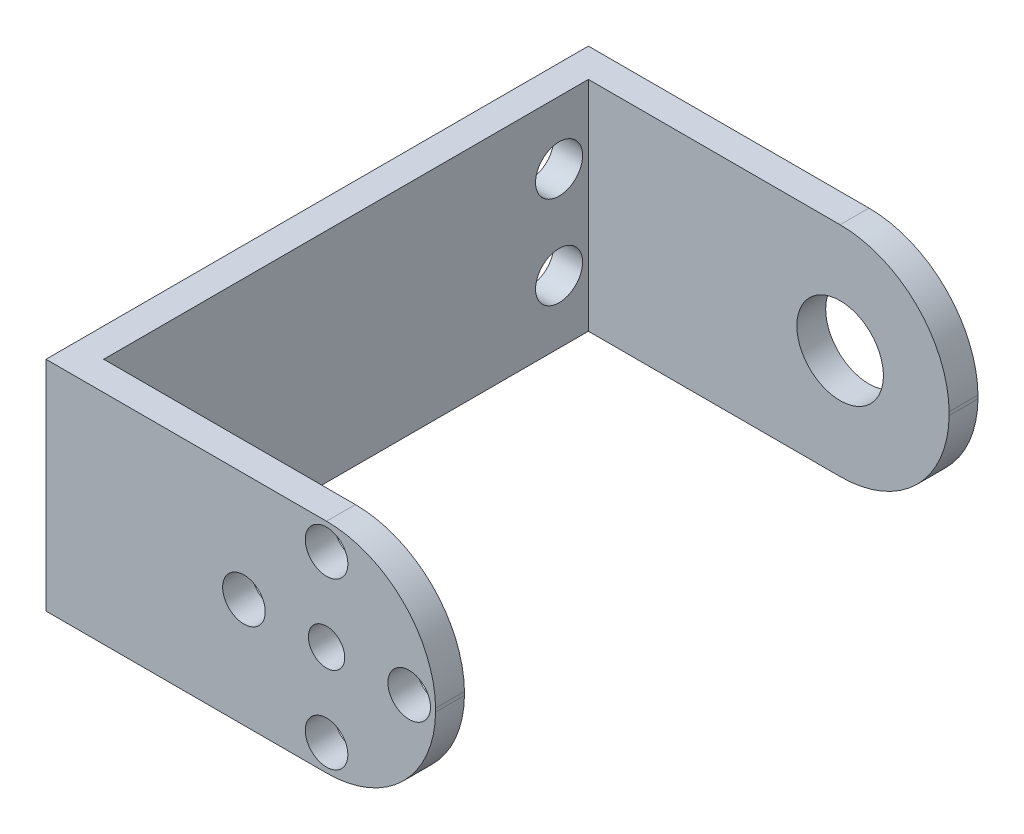
SolidWorks part; units mm, degrees
ref_plane "Front Plane" through (0, 0, 0) normal (0, 0, 1) x (1, 0, 0)
ref_plane "Top Plane" through (0, 0, 0) normal (0, 1, 0) x (1, 0, 0)
ref_plane "Right Plane" through (0, 0, 0) normal (1, 0, 0) x (0, 0, -1)
sketch "Sketch1" plane through (0, 0, 0) normal (0, 1, 0) x (1, 0, 0)
  line L0 (-21.4375, 0) -> (21.4375, 0) construction
  line L1 (21.4375, -29.845) -> (-21.4375, -29.845)
  line L2 (21.4375, -29.845) -> (21.4375, 29.845)
  line L3 (21.4375, 29.845) -> (-21.4375, 29.845)
  line L4 (-21.4375, -29.845) -> (-21.4375, 29.845)
  line L5 (21.4375, -29.845) -> (-21.4375, 29.845) construction
  line L6 (21.4375, 29.845) -> (-21.4375, -29.845) construction
  line L8 (21.4375, -26.67) -> (-18.2625, -26.67)
  line L10 (21.4375, 26.67) -> (-18.2625, 26.67)
  line L11 (-18.2625, -26.67) -> (-18.2625, 26.67)
  line L12 (19.9408, -16.2583) -> (-18.2625, 26.67) construction
  line L13 (13.9323, 9.5067) -> (-18.2625, -26.67) construction
  point P0 (0, 0)
  point P8 (5.472, 0)
  point P15 (-18.2625, 0)
  dimension "D1" = 59.69
  dimension "D2" = 42.875
  dimension "D3" = 53.34
  dimension "D4" = 39.7
extrude "Boss-Extrude1" add sketch "Sketch1" along normal blind 24.003 contours L8 L11 L10 L2 L3 L4 L1
sketch "Sketch2" plane through (0, 0, 29.845) normal (0, 0, 1) x (1, 0, 0)
  line L0 (-21.4375, 12.0015) -> (21.4375, 12.0015) construction
  line L1 (-21.4375, 24.003) -> (-21.4375, 0) construction
  line L2 (21.4375, 24.003) -> (21.4375, 0) construction
  line L3 (21.4375, 0) -> (-21.4375, 0) construction
  line L4 (21.4375, 24.003) -> (-21.4375, 24.003) construction
  line L5 (9.4375, 0) -> (15.0875, 0)
  line L7 (15.0875, 24.003) -> (9.4375, 24.003)
  arc A0 (9.4375, 0) -> (9.4375, 24.003) centre (9.4375, 12.0015) ccw
  point P6 (9.4375, 12.0015)
  dimension "D1" = 12
extrude "Cut-Extrude1" cut sketch "Sketch2" against normal through all
sketch "Sketch3" plane through (0, 0, 29.845) normal (0, 0, 1) x (1, 0, 0)
  line L0 (9.4375, 0) -> (9.4375, 24.003) construction
  circle A0 centre (9.4375, 12.0015) radius 2
  circle A1 centre (9.4375, 21.0947) radius 2.3432
  circle A2 centre (18.5307, 12.0015) radius 2.3432
  circle A3 centre (9.4375, 2.9083) radius 2.3432
  circle A4 centre (0.3443, 12.0015) radius 2.3432
  point P17 (3.0868, 12.0007)
  point P18 (9.4375, 12.0015)
  dimension "D1" = 4
  dimension "D2" = 9.0932
  dimension "D3" = 4
extrude "Cut-Extrude2" cut sketch "Sketch3" against normal up to next
sketch "Sketch4" plane through (0, 0, -29.845) normal (0, 0, -1) x (-1, 0, 0)
  line L0 (-9.4375, 24.003) -> (-9.4375, 0) construction
  line L1 (-9.4375, 0) -> (21.4375, 0) construction
  arc A0 (-21.4375, 11.8118) -> (-9.4375, 0) centre (-9.4375, 12.0015) ccw construction
  circle A1 centre (-9.4375, 12.0015) radius 4.7625
extrude "Cut-Extrude3" cut sketch "Sketch4" against normal up to next
sketch "Sketch5" plane through (-21.4375, 0, 0) normal (-1, 0, 0) x (0, 0, 1)
  line L0 (29.845, 12.0015) -> (-29.845, 12.0015) construction
  line L1 (29.845, 24.003) -> (29.845, 0) construction
  line L2 (-29.845, 24.003) -> (-29.845, 0) construction
  line L3 (0, 1.9725) -> (0, 22.0305) construction
  line L8 (20.443, 1.9725) -> (-20.443, 22.0305) construction
  line L9 (20.443, 22.0305) -> (-20.443, 1.9725) construction
  circle A0 centre (-23.443, 17.0815) radius 2.5868
  circle A1 centre (-23.443, 6.9215) radius 2.5868
  circle A2 centre (23.443, 6.9215) radius 2.5868
  circle A3 centre (23.443, 17.0815) radius 2.5868
  point P6 (0, 12.0015)
  dimension "D3" = 5.08
  dimension "D1" = 40.886
  dimension "D2" = 20.058
  dimension "D4" = 3
extrude "Cut-Extrude4" cut sketch "Sketch5" against normal up to next
